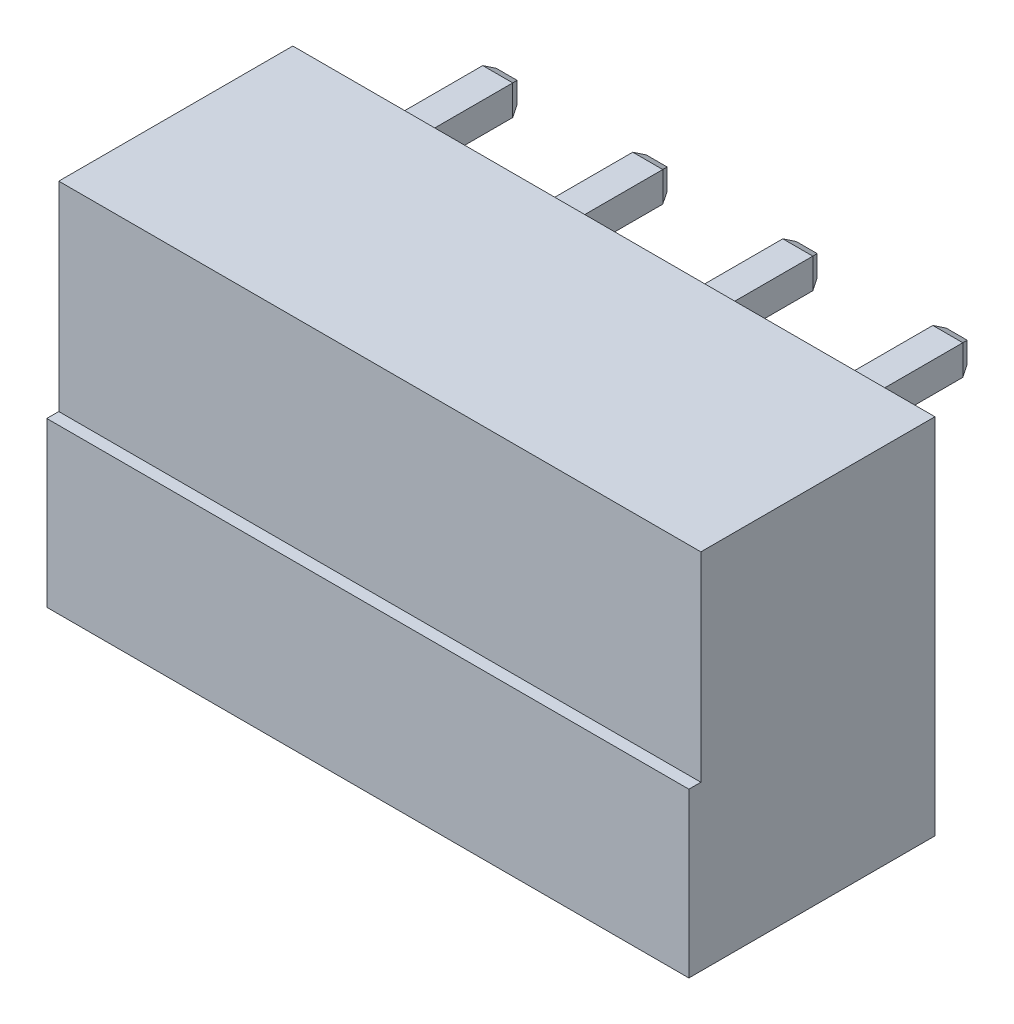
SolidWorks part; units mm, degrees
other "Детальный элемент1"
ref_plane "Спереди" through (0, 0, 0) normal (0, 0, 1) x (1, 0, 0)
ref_plane "Сверху" through (0, 0, 0) normal (0, 1, 0) x (1, 0, 0)
ref_plane "Справа" through (0, 0, 0) normal (1, 0, 0) x (0, 0, -1)
sketch "Эскиз1" plane through (0, 0, 0) normal (0, 0, 1) x (1, 0, 0)
  line L1 (-10.7, 12.1) -> (10.7, 12.1)
  line L2 (-10.7, 12.1) -> (-10.7, 0)
  line L3 (-10.7, 0) -> (10.7, 0)
  line L4 (10.7, 12.1) -> (10.7, 0)
  line L5 (-10.7, 12.1) -> (10.7, 0) construction
  line L6 (-10.7, 0) -> (10.7, 12.1) construction
  point P0 (0, 6.05)
  point P5 (0, 0)
  dimension "D1" = 12.1
  dimension "D2" = 21.4
extrude "Бобышка-Вытянуть1" add sketch "Эскиз1" along normal blind 8.2
sketch "Эскиз2" plane through (0, 0, 0) normal (0, -1, 0) x (1, 0, 0)
  line L0 (-10.07, 6.65) -> (-10.07, 1.7)
  line L1 (-10.07, 1.7) -> (-9.57, 1.7)
  line L2 (-10.07, 6.65) -> (-5.07, 6.65)
  line L3 (-5.07, 6.65) -> (-5.07, 1.7)
  line L4 (-5.07, 1.7) -> (-5.57, 1.7)
  line L5 (-7.57, 6.65) -> (-7.57, 0.7668) construction
  line L6 (-16.9007, 0.81) -> (1.7607, 0.81) construction
  line L7 (-10.7, 8.2) -> (-10.7, 0) construction
  line L8 (-10.7, 8.2) -> (10.7, 8.2) construction
  arc A0 (-5.57, 1.7) -> (-9.57, 1.7) centre (-7.57, 3.5022) cw
  point P10 (-7.57, 0.81)
  point P16 (0, 0)
  dimension "D1" = 4.95
  dimension "D2" = 5
  dimension "D3" = 5.84
  dimension "D4" = 0.63
  dimension "D5" = 1.55
  dimension "D6" = 0.5
extrude "Вырез-Вытянуть1" cut sketch "Эскиз2" against normal blind 8.66
sketch "Эскиз3" plane through (0, 8.66, 0) normal (0, -1, 0) x (1, 0, 0)
  line L2 (-10.07, 6.65) -> (-10.07, 1.7) construction
  line L3 (-5.07, 6.65) -> (-10.07, 6.65) construction
  line L4 (-10.7, 8.2) -> (-10.7, 0) construction
  circle A0 centre (-7.57, 4.1) radius 1.375
  point P6 (-10.07, 4.175)
  point P7 (-7.57, 6.65)
  point P8 (0, 0)
  point P11 (-10.7, 4.1)
  dimension "D1" = 2.75
extrude "Бобышка-Вытянуть2" add sketch "Эскиз3" along normal blind 2
chamfer "Фаска1" distance 0.6 angle 45 1 edges at (-6.195, 6.66, 4.1)
sketch "Эскиз4" plane through (0, 0, 8.2) normal (0, 0, 1) x (1, 0, 0)
  line L0 (10.7, 0) -> (10.7, 12.1) construction
  line L1 (-10.7, 12.1) -> (10.7, 12.1)
  line L2 (-10.7, 12.1) -> (-10.7, 5.45)
  line L3 (-10.7, 5.45) -> (10.7, 5.45)
  line L4 (10.7, 12.1) -> (10.7, 5.45)
  line L6 (-10.7, 0) -> (10.7, 0) construction
  dimension "D1" = 5.45
extrude "Вырез-Вытянуть2" cut sketch "Эскиз4" against normal blind 0.4
sketch "Эскиз5" plane through (0, 6.66, 0) normal (0, -1, 0) x (1, 0, 0)
  line L0 (-5.07, 6.65) -> (-10.07, 6.65) construction
  line L1 (-8.07, 4.6) -> (-7.07, 4.6)
  line L2 (-8.07, 4.6) -> (-8.07, 3.6)
  line L3 (-8.07, 3.6) -> (-7.07, 3.6)
  line L4 (-7.07, 4.6) -> (-7.07, 3.6)
  line L5 (-10.7, 8.2) -> (-10.7, 0) construction
  point P4 (-7.57, 4.6)
  point P7 (-7.57, 6.65)
  point P8 (-8.07, 4.1)
  point P11 (-10.7, 4.1)
  dimension "D1" = 1
extrude "Бобышка-Вытянуть3" add sketch "Эскиз5" along normal offset from surface (4.26 mm away) 2.4 separate body up to face at (-7.57, 0, 3.2017)
chamfer "Фаска2" distance 0.3 angle 63 4 edges at (-7.07, 2.4, 4.1) (-7.57, 2.4, 3.6) (-7.57, 2.4, 4.6) (-8.07, 2.4, 4.1)
sketch "Эскиз6" plane through (0, 0, 0) normal (0, 0, -1) x (-1, 0, 0)
  line L0 (5.07, 0) -> (10.07, 0) construction
  line L1 (7.07, 11) -> (8.07, 11)
  line L2 (7.07, 11) -> (7.07, 10)
  line L3 (7.07, 10) -> (8.07, 10)
  line L4 (8.07, 11) -> (8.07, 10)
  line L5 (-10.7, 12.1) -> (10.7, 12.1) construction
  point P4 (7.57, 10)
  point P7 (7.57, 0)
  point P8 (8.07, 10.5)
  dimension "D1" = 1
  dimension "D2" = 1.6
extrude "Бобышка-Вытянуть4" add sketch "Эскиз6" along normal blind 4 separate body
chamfer "Фаска3" distance 0.3 angle 27 4 edges at (-7.57, 11, -4) (-7.07, 10.5, -4) (-7.57, 10, -4) (-8.07, 10.5, -4)
pattern_linear "Линейный массив1" count 4 spacing 5 along (1, 0, 0) of "Вырез-Вытянуть1", "Бобышка-Вытянуть2", "Фаска1"
pattern_linear "Линейный массив2" count 4 spacing 5 along (1, 0, 0) of bodies 112 111
equation "\"N\"= 4"
equation "\"D2@Эскиз1\"=5*\"N\"+1.4"
equation "\"D1@Линейный массив1\"=\"N\""
equation "\"D1@Линейный массив2\"=\"N\""
